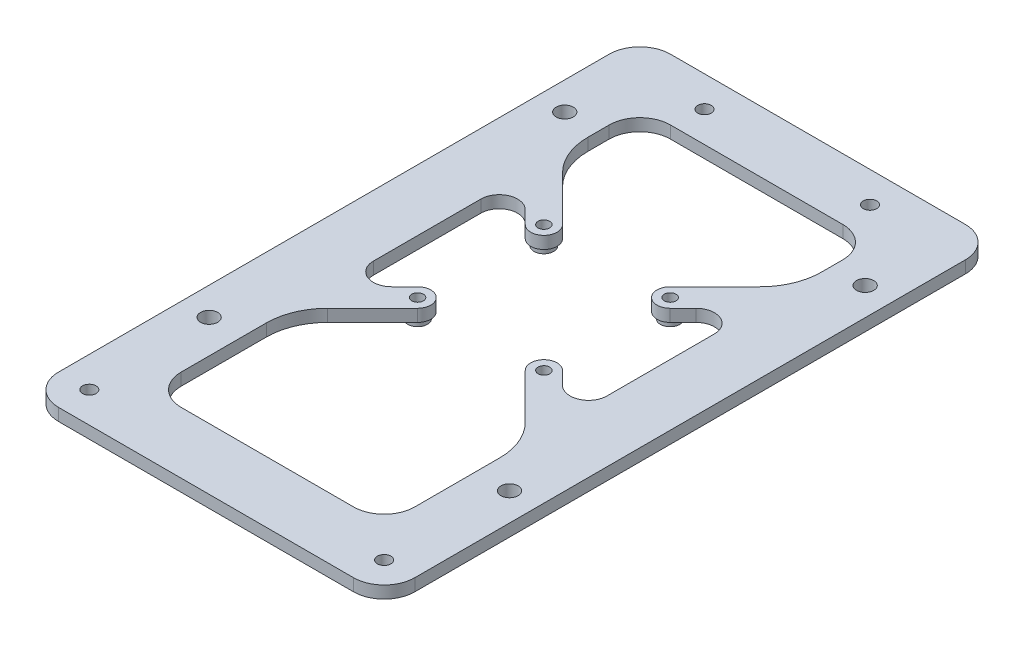
SolidWorks part; units mm, degrees
ref_plane "Front Plane" through (0, 0, 0) normal (0, 0, 1) x (1, 0, 0)
ref_plane "Top Plane" through (0, 0, 0) normal (0, 1, 0) x (1, 0, 0)
ref_plane "Right Plane" through (0, 0, 0) normal (1, 0, 0) x (0, 0, -1)
sketch "Sketch1" plane through (0, 0, 0) normal (0, 1, 0) x (1, 0, 0)
  line L4 (13, 13) -> (-13, 13)
  line L5 (13, -13) -> (13, 13)
  line L6 (-13, -13) -> (13, -13)
  line L7 (-13, 13) -> (-13, -13)
  line L8 (13, 13) -> (-13, 13)
  line L9 (13, -13) -> (13, 13)
  line L10 (-13, -13) -> (13, -13)
  line L11 (-13, 13) -> (-13, -13)
  circle A1 centre (13.5, 39.7) radius 0.95
  circle A2 centre (13.5, 39.7) radius 0.95
  circle A3 centre (-13.5, 39.7) radius 0.95
  circle A4 centre (-13.5, 39.7) radius 0.95
  circle A5 centre (-24.05, -50.1) radius 0.95
  circle A6 centre (-24.05, -50.1) radius 0.95
  circle A7 centre (24.05, -50.1) radius 0.95
  circle A8 centre (24.05, -50.1) radius 0.95
  circle A9 centre (-10.3, -10.3) radius 1.7
  circle A10 centre (-10.3, -10.3) radius 1.7
  circle A11 centre (10.3, 10.3) radius 1.7
  circle A12 centre (10.3, 10.3) radius 1.7
  circle A13 centre (-10.3, 10.3) radius 1.7
  circle A14 centre (-10.3, 10.3) radius 1.7
  circle A15 centre (10.3, -10.3) radius 1.7
  circle A16 centre (10.3, -10.3) radius 1.7
  dimension "D1" = 0
  dimension "D2" = 0
  dimension "D3" = 0
  dimension "D4" = 0
  dimension "D5" = 0
  dimension "D6" = 0
  dimension "D7" = 0
  dimension "D8" = 0
  dimension "D9" = 0
sketch "Sketch2" plane through (0, 0, 0) normal (0, 1, 0) x (1, 0, 0)
  line L0 (-29.05, 44.7) -> (-29.05, -55.1)
  line L1 (-24.05, 39.7) -> (24.05, 39.7) construction
  line L2 (-24.05, 39.7) -> (-24.05, -50.1) construction
  line L3 (-24.05, -50.1) -> (24.05, -50.1) construction
  line L4 (24.05, 39.7) -> (24.05, -50.1) construction
  line L5 (-29.05, -55.1) -> (29.05, -55.1)
  line L6 (29.05, 44.7) -> (29.05, -55.1)
  line L7 (-29.05, 44.7) -> (29.05, 44.7)
  line L8 (-19.05, 34.7) -> (-19.05, -45.1)
  line L9 (-19.05, -45.1) -> (19.05, -45.1)
  line L10 (19.05, 34.7) -> (19.05, -45.1)
  line L11 (-19.05, 34.7) -> (19.05, 34.7)
  line L12 (24.05, 24.05) -> (-24.05, -24.05) construction
  line L13 (-24.05, 24.05) -> (24.05, -24.05) construction
  line L15 (-24.5, 27.9) -> (24.5, 27.9) construction
  line L16 (-24.5, 27.9) -> (-24.5, -30.1) construction
  line L17 (-24.5, -30.1) -> (24.5, -30.1) construction
  line L18 (24.5, 27.9) -> (24.5, -30.1) construction
  circle A0 centre (-24.05, -50.1) radius 1.1
  circle A1 centre (24.05, -50.1) radius 1.1
  circle A2 centre (-13.5, 39.7) radius 1.1
  circle A3 centre (13.5, 39.7) radius 1.1
  circle A4 centre (-10.3, 10.3) radius 0.95
  circle A5 centre (-10.3, -10.3) radius 0.95
  circle A6 centre (10.3, -10.3) radius 0.95
  circle A7 centre (10.3, 10.3) radius 0.95
  circle A8 centre (24.05, -50.1) radius 0.95 construction
  circle A9 centre (24.5, 27.9) radius 1.4
  circle A10 centre (-24.5, 27.9) radius 1.4
  circle A11 centre (24.5, -30.1) radius 1.4
  circle A12 centre (-24.5, -30.1) radius 1.4
  point P44 (0, 27.9)
  dimension "D3" = 2.2
  dimension "D7" = 2.8
  dimension "D4" = 49
  dimension "D5" = 58
  dimension "D6" = 25
  dimension "D1" = 5
  dimension "D2" = 5
sketch "Sketch3" plane through (0, 0, 0) normal (0, 1, 0) x (1, 0, 0)
  line L0 (-24.05, 24.05) -> (24.05, -24.05) construction
  line L1 (24.05, 24.05) -> (-24.05, -24.05) construction
  line L2 (-24.05, 24.05) -> (24.05, -24.05) construction
  line L3 (24.05, 24.05) -> (-24.05, -24.05) construction
  line L4 (-29.05, 44.7) -> (-29.05, -55.1)
  line L5 (-29.05, -55.1) -> (29.05, -55.1)
  line L6 (29.05, -55.1) -> (29.05, 44.7)
  line L7 (29.05, 44.7) -> (-29.05, 44.7)
  line L8 (-29.05, 44.7) -> (-29.05, -55.1)
  line L9 (-29.05, -55.1) -> (29.05, -55.1)
  line L10 (29.05, -55.1) -> (29.05, 44.7)
  line L11 (29.05, 44.7) -> (-29.05, 44.7)
  line L12 (19.05, -45.1) -> (19.05, 34.7)
  line L13 (-19.05, -45.1) -> (19.05, -45.1)
  line L14 (-19.05, 34.7) -> (-19.05, -45.1)
  line L15 (19.05, 34.7) -> (-19.05, 34.7)
  line L16 (19.05, -45.1) -> (19.05, -22.0906)
  line L17 (-19.05, -45.1) -> (19.05, -45.1)
  line L18 (-19.05, 34.7) -> (-19.05, 22.0906)
  line L19 (19.05, 34.7) -> (-19.05, 34.7)
  line L20 (19.05, 22.0906) -> (8.7797, 11.8203)
  line L21 (-19.05, 16.0094) -> (-11.8203, 8.7797)
  line L22 (19.05, 16.0094) -> (11.8203, 8.7797)
  line L23 (-19.05, 22.0906) -> (-8.7797, 11.8203)
  line L24 (11.8203, -8.7797) -> (19.05, -16.0094)
  line L25 (-22.5297, 25.5703) -> (25.5703, -22.5297) construction
  line L26 (-11.8203, -8.7797) -> (-19.05, -16.0094)
  line L27 (22.5297, 25.5703) -> (-25.5703, -22.5297) construction
  line L28 (-8.7797, -11.8203) -> (-19.05, -22.0906)
  line L29 (25.5703, 22.5297) -> (-22.5297, -25.5703) construction
  line L30 (-19.05, 16.0094) -> (-19.05, -16.0094)
  line L31 (-25.5703, 22.5297) -> (22.5297, -25.5703) construction
  line L32 (8.7797, -11.8203) -> (19.05, -22.0906)
  line L33 (-19.05, -22.0906) -> (-19.05, -45.1)
  line L34 (19.05, -16.0094) -> (19.05, 16.0094)
  line L35 (19.05, 22.0906) -> (19.05, 34.7)
  arc A0 (8.7797, 11.8203) -> (11.8203, 8.7797) centre (10.3, 10.3) ccw
  circle A1 centre (24.05, -50.1) radius 1.1
  circle A2 centre (24.05, -50.1) radius 1.1
  circle A3 centre (-10.3, -10.3) radius 0.95
  circle A4 centre (-10.3, -10.3) radius 0.95
  circle A5 centre (13.5, 39.7) radius 1.1
  circle A6 centre (13.5, 39.7) radius 1.1
  circle A7 centre (-13.5, 39.7) radius 1.1
  circle A8 centre (-13.5, 39.7) radius 1.1
  circle A9 centre (-24.05, -50.1) radius 1.1
  circle A10 centre (-24.05, -50.1) radius 1.1
  circle A11 centre (-24.5, 27.9) radius 1.4
  circle A12 centre (-24.5, 27.9) radius 1.4
  circle A13 centre (24.5, 27.9) radius 1.4
  circle A14 centre (24.5, 27.9) radius 1.4
  circle A15 centre (10.3, 10.3) radius 0.95
  circle A16 centre (10.3, 10.3) radius 0.95
  circle A17 centre (10.3, -10.3) radius 0.95
  circle A18 centre (10.3, -10.3) radius 0.95
  circle A19 centre (-10.3, 10.3) radius 0.95
  circle A20 centre (-10.3, 10.3) radius 0.95
  circle A21 centre (-24.5, -30.1) radius 1.4
  circle A22 centre (-24.5, -30.1) radius 1.4
  circle A23 centre (24.5, -30.1) radius 1.4
  circle A24 centre (24.5, -30.1) radius 1.4
  arc A25 (11.8203, -8.7797) -> (8.7797, -11.8203) centre (10.3, -10.3) ccw
  arc A26 (-8.7797, -11.8203) -> (-11.8203, -8.7797) centre (-10.3, -10.3) ccw
  arc A27 (-11.8203, 8.7797) -> (-8.7797, 11.8203) centre (-10.3, 10.3) ccw
  dimension "D17" = 2.15
  dimension "D1" = 0
  dimension "D2" = 0
  dimension "D3" = 0
  dimension "D4" = 0
  dimension "D5" = 0
  dimension "D6" = 0
  dimension "D7" = 0
  dimension "D8" = 0
  dimension "D9" = 0
  dimension "D10" = 0
  dimension "D11" = 0
  dimension "D12" = 0
  dimension "D13" = 0
  dimension "D14" = 0
  dimension "D15" = 2.15
  dimension "D16" = 2.15
extrude "Boss-Extrude1" add sketch "Sketch3" along normal blind 2
fillet "Fillet1" radius 5 8 edges at (19.05, 1, 45.1) (-19.05, 1, 45.1) (19.05, 1, -34.7) (-29.05, 1, -44.7) (-19.05, 1, -34.7) (29.05, 1, -44.7) (29.05, 1, 55.1) (-29.05, 1, 55.1)
fillet "Fillet2" radius 3 4 edges at (-19.05, 1, 16.0094) (-19.05, 1, -16.0094) (19.05, 1, -16.0094) (19.05, 1, 16.0094)
fillet "Fillet3" radius 10 4 edges at (-19.05, 1, -22.0906) (-19.05, 1, 22.0906) (19.05, 1, -22.0906) (19.05, 1, 22.0906)
sketch "Sketch4" plane through (0, 0, 0) normal (0, -1, 0) x (1, 0, 0)
  circle A0 centre (-10.3, 10.3) radius 1.6
  circle A1 centre (10.3, 10.3) radius 1.6
  circle A2 centre (10.3, -10.3) radius 1.6
  circle A3 centre (-10.3, -10.3) radius 1.6
  circle A4 centre (-10.3, -10.3) radius 0.95 construction
  circle A5 centre (10.3, -10.3) radius 0.95 construction
  circle A6 centre (10.3, 10.3) radius 0.95 construction
  circle A7 centre (-10.3, 10.3) radius 0.95 construction
  circle A8 centre (-10.3, -10.3) radius 0.95
  circle A9 centre (10.3, -10.3) radius 0.95
  circle A10 centre (10.3, 10.3) radius 0.95
  circle A11 centre (-10.3, 10.3) radius 0.95
  dimension "D1" = 3.2
extrude "Boss-Extrude2" add sketch "Sketch4" along normal blind 1
